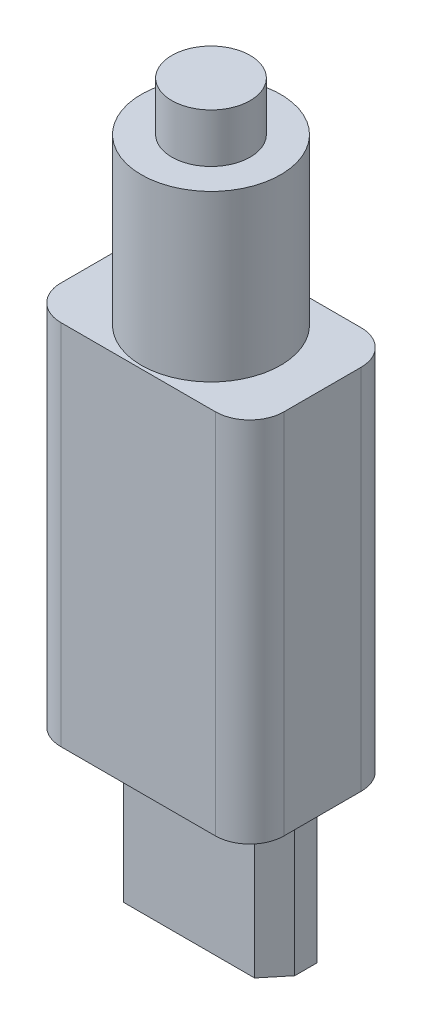
SolidWorks part; units mm, degrees
ref_plane "Front Plane" through (0, 0, 0) normal (0, 0, 1) x (1, 0, 0)
ref_plane "Top Plane" through (0, 0, 0) normal (0, 1, 0) x (1, 0, 0)
ref_plane "Right Plane" through (0, 0, 0) normal (1, 0, 0) x (0, 0, -1)
sketch "Sketch1" plane through (0, 0, 0) normal (0, 1, 0) x (1, 0, 0)
  line L0 (-3.42, 0) -> (-2.68, -0.9)
  line L1 (-2.68, -0.9) -> (2.68, -0.9)
  line L2 (-3.42, 0) -> (-3.42, 0.9)
  line L3 (-3.42, 0.9) -> (3.42, 0.9)
  line L4 (3.42, 0) -> (3.42, 0.9)
  line L5 (-3.42, -0.9) -> (3.42, 0.9) construction
  line L6 (-3.42, 0.9) -> (3.42, -0.9) construction
  line L7 (2.68, -0.9) -> (3.42, 0)
  line L8 (0, 0) -> (0, -0.9) construction
  point P0 (0, 0)
  dimension "D1" = 6.84
  dimension "D2" = 1.8
  dimension "D3" = 5.36
  dimension "D4" = 0.9
extrude "Boss-Extrude1" add sketch "Sketch1" along normal blind 6.3
sketch "Sketch2" plane through (0, 6.3, 0) normal (0, 1, 0) x (1, 0, 0)
  line L1 (-4.555, -2.975) -> (4.555, -2.975)
  line L2 (-4.555, -2.975) -> (-4.555, 2.975)
  line L3 (-4.555, 2.975) -> (4.555, 2.975)
  line L4 (4.555, -2.975) -> (4.555, 2.975)
  line L5 (-4.555, -2.975) -> (4.555, 2.975) construction
  line L6 (-4.555, 2.975) -> (4.555, -2.975) construction
  point P0 (0, 0)
  dimension "D1" = 5.95
  dimension "D2" = 9.11
extrude "Boss-Extrude2" add sketch "Sketch2" along normal blind 15
fillet "Fillet1" radius 1.4 4 edges at (4.555, 13.8, -2.975) (-4.555, 13.8, -2.975) (-4.555, 13.8, 2.975) (4.555, 13.8, 2.975)
sketch "Sketch4" plane through (0, 21.3, 0) normal (0, 1, 0) x (1, 0, 0)
  circle A0 centre (0, 0) radius 2.845
  dimension "D1" = 5.69
extrude "Boss-Extrude3" add sketch "Sketch4" along normal blind 6.74
sketch "Sketch5" plane through (0, 28.04, 0) normal (0, 1, 0) x (1, 0, 0)
  circle A0 centre (0, 0) radius 1.6
  dimension "D1" = 3.2
extrude "Boss-Extrude4" add sketch "Sketch5" along normal blind 2
